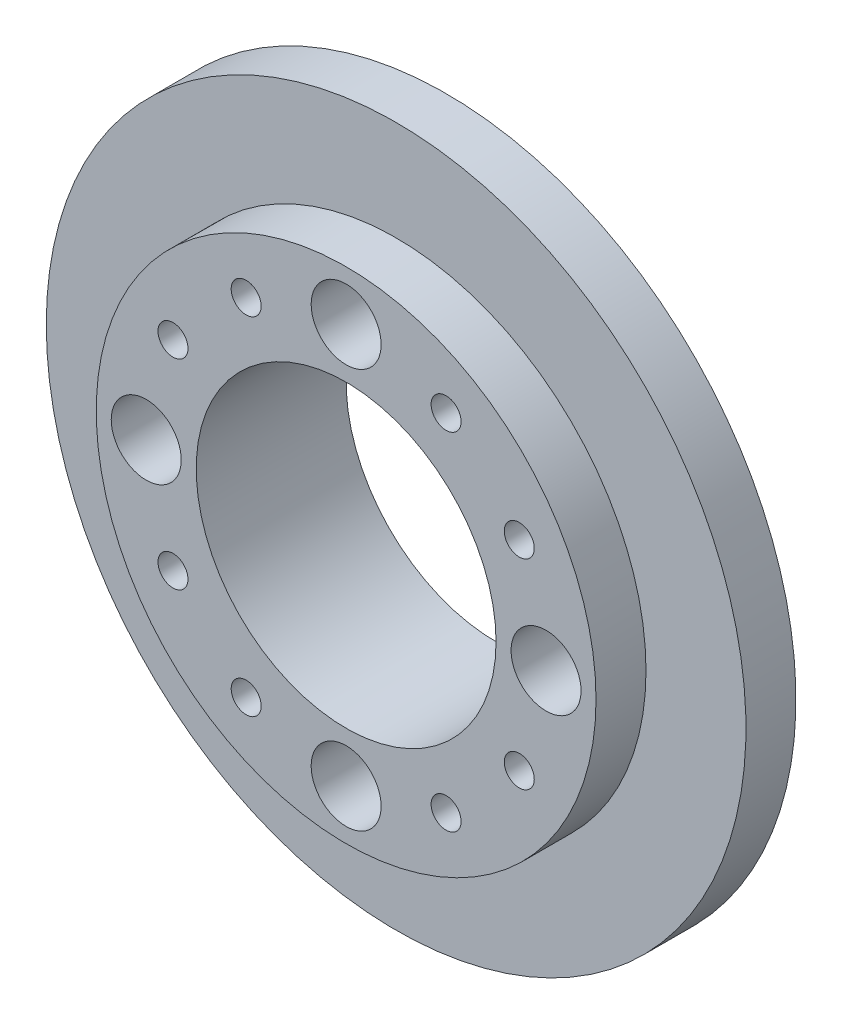
SolidWorks part; units mm, degrees
ref_plane "前视基准面" through (0, 0, 0) normal (0, 0, 1) x (1, 0, 0)
ref_plane "上视基准面" through (0, 0, 0) normal (0, 1, 0) x (1, 0, 0)
ref_plane "右视基准面" through (0, 0, 0) normal (1, 0, 0) x (0, 0, -1)
other "Configuration Table"
sketch "Sketch1" plane through (0, 0, 0) normal (0, 0, 1) x (1, 0, 0)
  circle A1 centre (0, 0) radius 12.5
  dimension "D2" = 25
extrude "Boss-Extrude1" add sketch "Sketch1" along normal blind 2.5
sketch "Sketch3" plane through (0, 0, 0) normal (0, 0, -1) x (-1, 0, 0)
  circle A0 centre (0, 0) radius 17.5
  dimension "D1" = 35
extrude "Boss-Extrude2" add sketch "Sketch3" along normal blind 2.5
sketch "Sketch5" plane through (0, 0, -2.5) normal (0, 0, -1) x (-1, 0, 0)
  circle A0 centre (0, 0) radius 12.5
  dimension "D1" = 25
extrude "Boss-Extrude3" add sketch "Sketch5" along normal blind 2.5
sketch "Sketch2" plane through (0, 0, 2.5) normal (0, 0, 1) x (1, 0, 0)
  circle A0 centre (0, 0) radius 10 construction
  circle A1 centre (0, 10) radius 0.75
  circle A2 centre (0, 0) radius 10 construction
  circle A3 centre (5, 8.6603) radius 0.75
  circle A4 centre (0, 0) radius 10 construction
  circle A5 centre (8.6603, 5) radius 0.75
  circle A6 centre (0, 0) radius 10 construction
  circle A7 centre (10, 0) radius 0.75
  circle A8 centre (0, 0) radius 10 construction
  circle A9 centre (8.6603, -5) radius 0.75
  circle A10 centre (0, 0) radius 10 construction
  circle A11 centre (5, -8.6603) radius 0.75
  circle A12 centre (0, 0) radius 10 construction
  circle A13 centre (0, -10) radius 0.75
  circle A14 centre (0, 0) radius 10 construction
  circle A15 centre (-5, -8.6603) radius 0.75
  circle A16 centre (0, 0) radius 10 construction
  circle A17 centre (-8.6603, -5) radius 0.75
  circle A18 centre (0, 0) radius 10 construction
  circle A19 centre (-10, 0) radius 0.75
  circle A20 centre (0, 0) radius 10 construction
  circle A21 centre (-8.6603, 5) radius 0.75
  circle A22 centre (0, 0) radius 10 construction
  circle A23 centre (-5, 8.6603) radius 0.75
  circle A24 centre (0, 0) radius 7.5
  point P40 (0, 0)
  dimension "D1" = 20
  dimension "D2" = 1.5
  dimension "D4" = 15
  dimension "D3" = 12
extrude "Cut-Extrude1" cut sketch "Sketch2" against normal through all both and the other way through all
sketch "Sketch6" plane through (0, 0, -5) normal (0, 0, -1) x (-1, 0, 0)
  circle A0 centre (0, 10) radius 1.75
  circle A1 centre (10, 0) radius 1.75
  circle A2 centre (0, -10) radius 1.75
  circle A3 centre (-10, 0) radius 1.75
  point P12 (0, 0)
  dimension "D1" = 3.5
  dimension "D2" = 4
extrude "Cut-Extrude2" cut sketch "Sketch6" against normal blind 10
